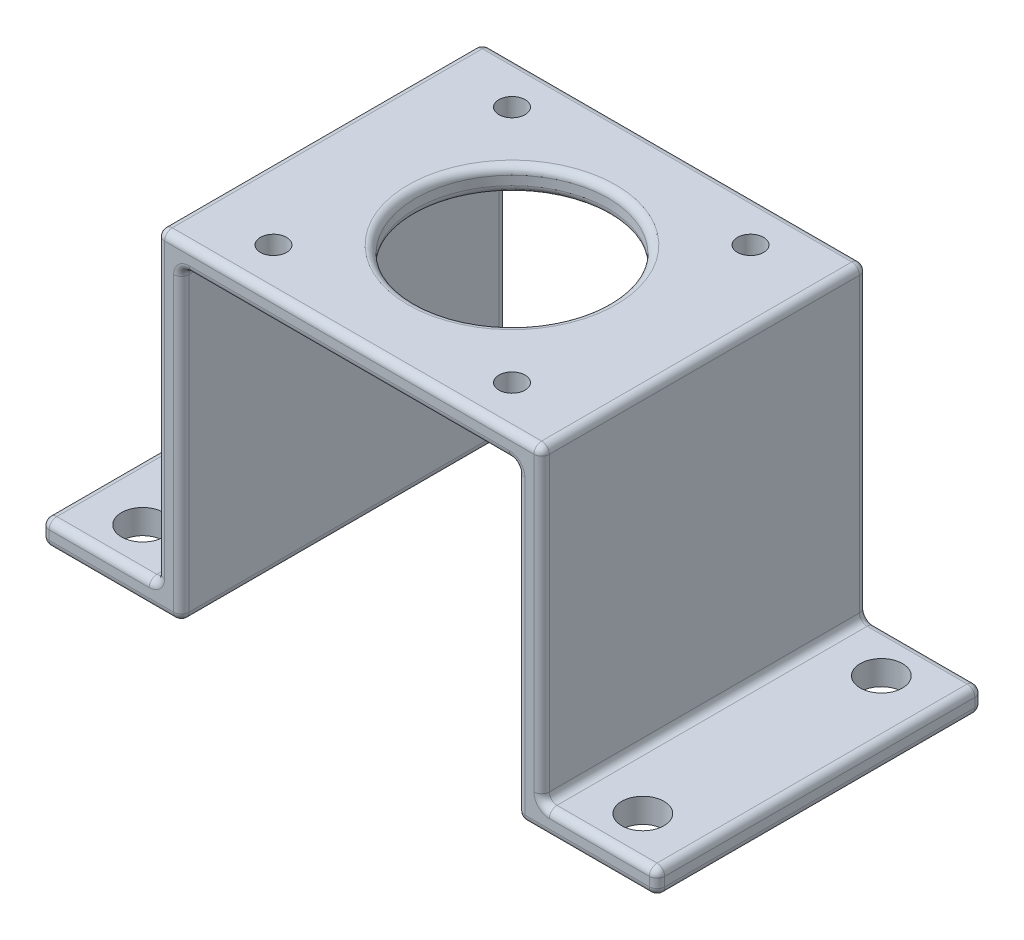
SolidWorks part; units mm, degrees
ref_plane "Front Plane" through (0, 0, 0) normal (0, 0, 1) x (1, 0, 0)
ref_plane "Top Plane" through (0, 0, 0) normal (0, 1, 0) x (1, 0, 0)
ref_plane "Right Plane" through (0, 0, 0) normal (1, 0, 0) x (0, 0, -1)
sketch "Sketch1" plane through (0, 0, 0) normal (0, 1, 0) x (1, 0, 0)
  line L1 (25, -21.15) -> (-25, -21.15)
  line L2 (25, -21.15) -> (25, 21.15)
  line L3 (25, 21.15) -> (-25, 21.15)
  line L4 (-25, -21.15) -> (-25, 21.15)
  line L5 (25, -21.15) -> (-25, 21.15) construction
  line L6 (25, 21.15) -> (-25, -21.15) construction
  line L7 (15.5, -15.5) -> (-15.5, -15.5) construction
  line L8 (15.5, -15.5) -> (15.5, 15.5) construction
  line L9 (15.5, 15.5) -> (-15.5, 15.5) construction
  line L10 (-15.5, -15.5) -> (-15.5, 15.5) construction
  line L11 (15.5, -15.5) -> (-15.5, 15.5) construction
  line L12 (15.5, 15.5) -> (-15.5, -15.5) construction
  circle A0 centre (0, 0) radius 12.5
  circle A1 centre (-15.5, 15.5) radius 1.7
  circle A2 centre (15.5, 15.5) radius 1.7
  circle A3 centre (15.5, -15.5) radius 1.7
  circle A4 centre (-15.5, -15.5) radius 1.7
  point P0 (0, 0)
  dimension "D3" = 25
  dimension "D5" = 3.4
  dimension "D1" = 50
  dimension "D2" = 42.3
  dimension "D4" = 31
extrude "Boss-Extrude1" add sketch "Sketch1" along normal blind 3.175
sketch "Sketch2" plane through (0, 0, 0) normal (0, -1, 0) x (1, 0, 0)
  line L0 (25, -21.15) -> (-25, -21.15) construction
  line L1 (-25, 21.15) -> (-21.825, 21.15)
  line L2 (-25, 21.15) -> (-25, -21.15)
  line L3 (-25, -21.15) -> (-21.825, -21.15)
  line L4 (-21.825, 21.15) -> (-21.825, -21.15)
  line L5 (-25, 21.15) -> (25, 21.15) construction
  line L6 (25, -21.15) -> (21.825, -21.15)
  line L7 (25, -21.15) -> (25, 21.15)
  line L8 (25, 21.15) -> (21.825, 21.15)
  line L9 (21.825, -21.15) -> (21.825, 21.15)
  dimension "D1" = 3.175
extrude "Boss-Extrude2" add sketch "Sketch2" along normal blind 40
sketch "Sketch3" plane through (0, -40, 0) normal (0, -1, 0) x (1, 0, 0)
  line L0 (-25, -21.15) -> (-21.825, -21.15) construction
  line L1 (-25, 21.15) -> (-40, 21.15)
  line L2 (-25, 21.15) -> (-25, -21.15)
  line L3 (-25, -21.15) -> (-40, -21.15)
  line L4 (-40, 21.15) -> (-40, -21.15)
  line L5 (25, 21.15) -> (40, 21.15)
  line L6 (25, 21.15) -> (25, -21.15)
  line L7 (25, -21.15) -> (40, -21.15)
  line L8 (40, 21.15) -> (40, -21.15)
  line L9 (-32.5, 21.15) -> (-32.5, 15.5) construction
  line L10 (-32.5, 15.5) -> (-32.5, -15.5) construction
  line L11 (-32.5, -15.5) -> (-32.5, -21.15) construction
  line L12 (32.5, -21.15) -> (32.5, -15.5) construction
  line L13 (32.5, -15.5) -> (32.5, 15.5) construction
  line L14 (32.5, 15.5) -> (32.5, 21.15) construction
  circle A0 centre (-32.5, 15.5) radius 2.75
  circle A1 centre (-32.5, -15.5) radius 2.75
  circle A2 centre (32.5, -15.5) radius 2.75
  circle A3 centre (32.5, 15.5) radius 2.75
  dimension "D3" = 5.5
  dimension "D1" = 15
  dimension "D2" = 31
extrude "Boss-Extrude3" add sketch "Sketch3" against normal blind 3.175
fillet "Fillet1" radius 1 36 edges at (-25, 3.175, 0) (-25, -36.825, 0) (25, 3.175, 0) (25, -36.825, 0) (-21.825, 0, 0) (-21.825, -40, 0) (21.825, 0, 0) (21.825, -40, 0) (40, -36.825, 0) (40, -40, 0) (0, 3.175, -21.15) (-25, -16.825, -21.15) (-32.5, -36.825, -21.15) (-30.9125, -40, -21.15) (-21.825, -20, -21.15) (0, 0, -21.15) (21.825, -20, -21.15) (30.9125, -40, -21.15) (40, -38.4125, -21.15) (32.5, -36.825, -21.15) (25, -16.825, -21.15) (0, 3.175, 21.15) (25, -16.825, 21.15) (32.5, -36.825, 21.15) (40, -38.4125, 21.15) (30.9125, -40, 21.15) (21.825, -20, 21.15) (0, 0, 21.15) (-21.825, -20, 21.15) (-30.9125, -40, 21.15) (-32.5, -36.825, 21.15) (-25, -16.825, 21.15) (-40, -38.4125, -21.15) (-40, -36.825, 0) (-40, -38.4125, 21.15) (-40, -40, 0)
fillet "Fillet2" radius 1 2 edges at (0, 0, 12.5) (0, 3.175, 12.5)
